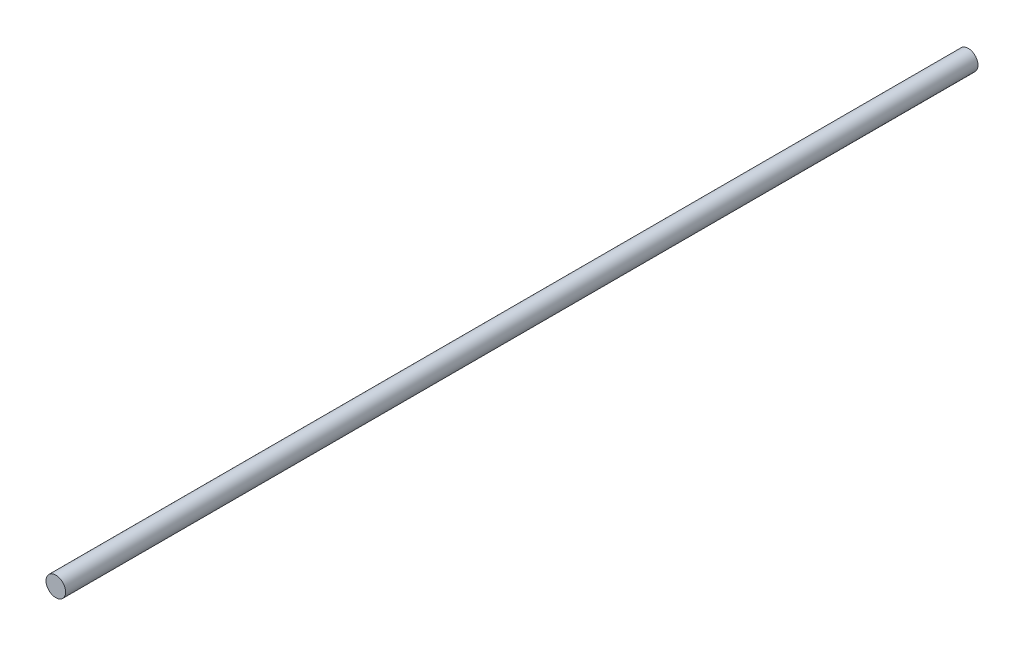
SolidWorks part; units mm, degrees
material "Aço inoxidável forjado"
ref_plane "Plano frontal" through (0, 0, 0) normal (0, 0, 1) x (1, 0, 0)
ref_plane "Plano superior" through (0, 0, 0) normal (0, 1, 0) x (1, 0, 0)
ref_plane "Plano direito" through (0, 0, 0) normal (1, 0, 0) x (0, 0, -1)
sketch "Esboço1" plane through (0, 0, 0) normal (0, 0, 1) x (1, 0, 0)
  circle A0 centre (0, 0) radius 4
  dimension "D1" = 8
extrude "Ressalto-extrusão1" add sketch "Esboço1" along normal blind 372 contours A0
